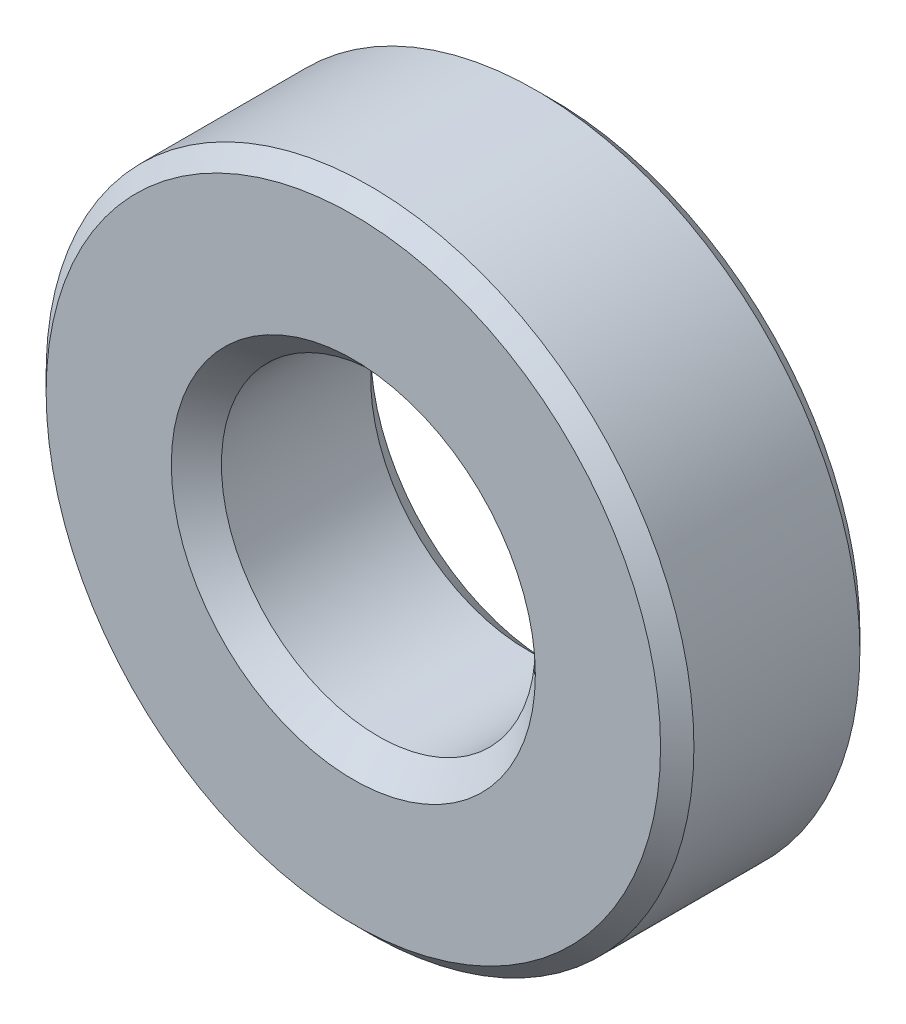
SolidWorks part; units mm, degrees
ref_plane "Front Plane" through (0, 0, 0) normal (0, 0, 1) x (1, 0, 0)
ref_plane "Top Plane" through (0, 0, 0) normal (0, 1, 0) x (1, 0, 0)
ref_plane "Right Plane" through (0, 0, 0) normal (1, 0, 0) x (0, 0, -1)
sketch "Sketch1" plane through (0, 0, 0) normal (0, 0, 1) x (1, 0, 0)
  circle A0 centre (0, 0) radius 6.5 construction
  circle A1 centre (0, 0) radius 3.15 construction
  point P4 (0, 6.5)
  dimension "ID" = 6.3
  dimension "OD" = 13
sketch "Sketch2" plane through (0, 0, 0) normal (1, 0, 0) x (0, 0, -1)
  line L0 (-2, 6.5) -> (2, 6.5) construction
  dimension "Length" = 4
sketch "Sketch3" plane through (0, 0, 0) normal (0, 0, 1) x (1, 0, 0)
  circle A0 centre (0, 0) radius 3.15 construction
  circle A1 centre (0, 0) radius 6.5 construction
  circle A2 centre (0, 0) radius 3.15
  circle A3 centre (0, 0) radius 6.5
extrude "Boss-Extrude1" add sketch "Sketch3" against normal up to vertex (2 mm away) and the other way up to vertex (2 mm away) up to point (0, 6.5, -2) other way up to point (0, 6.5, 2)
chamfer "Chamfer1" distance 0.335 angle 45 2 edges at (6.5, 0, 2) (6.5, 0, -2)
chamfer "Chamfer2" distance 0.5025 angle 45 2 edges at (3.15, 0, 2) (3.15, 0, -2)
sketch "Sketch4" plane through (0, 0, 2) normal (0, 0, 1) x (1, 0, 0)
  circle A0 centre (0, 0) radius 3.6525 construction
  circle A1 centre (0, 0) radius 6.165 construction
  circle A2 centre (0, 0) radius 3.6525
  circle A3 centre (0, 0) radius 6.165
equation "\"D1@Chamfer1\"=(\"OD@Sketch1\"-\"ID@Sketch1\")*0.05"
equation "\"D1@Chamfer2\"=(\"OD@Sketch1\"-\"ID@Sketch1\")*0.075"
